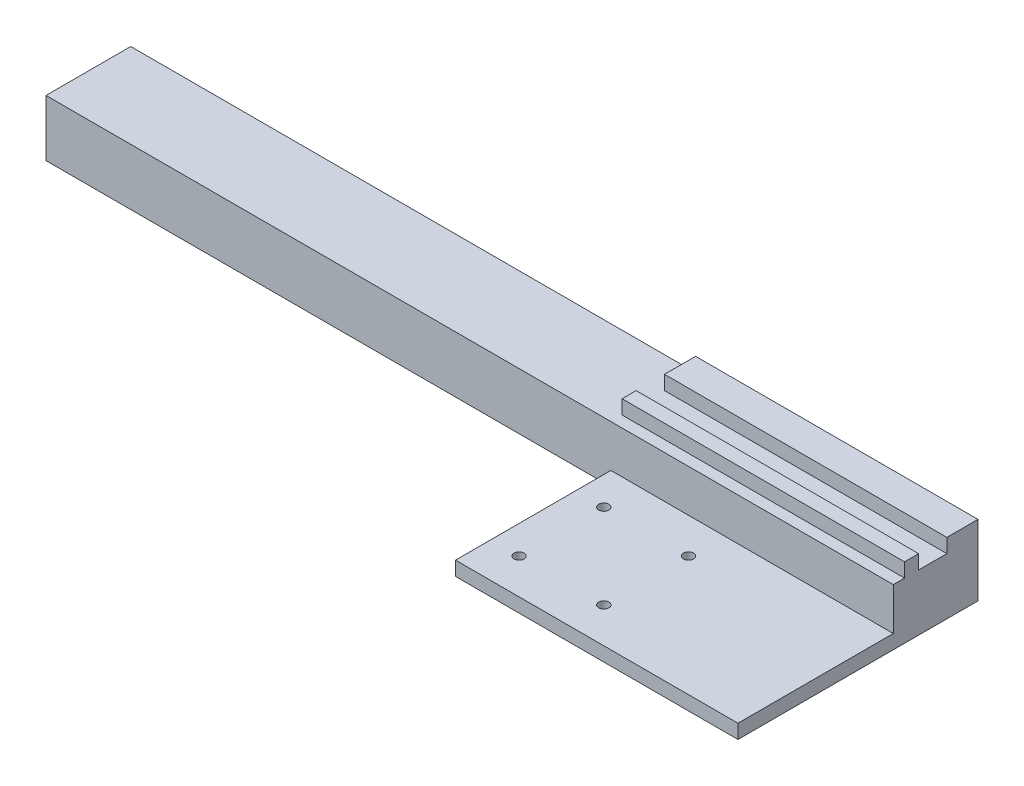
SolidWorks part; units mm, degrees
ref_plane "Front Plane" through (0, 0, 0) normal (0, 0, 1) x (1, 0, 0)
ref_plane "Top Plane" through (0, 0, 0) normal (0, 1, 0) x (1, 0, 0)
ref_plane "Right Plane" through (0, 0, 0) normal (1, 0, 0) x (0, 0, -1)
sketch "Sketch1" plane through (0, 0, 0) normal (0, 1, 0) x (1, 0, 0)
  line L1 (0, 0) -> (100, 0)
  line L2 (0, 0) -> (0, -55)
  line L3 (0, -55) -> (100, -55)
  line L4 (100, 0) -> (100, -55)
  dimension "D1" = 100
  dimension "D2" = 55
extrude "Boss-Extrude1" add sketch "Sketch1" along normal blind 5
sketch "Sketch3" plane through (0, 5, 0) normal (0, 1, 0) x (1, 0, 0)
  line L0 (100, 0) -> (0, 0) construction
  line L1 (0, -27.5) -> (100, -27.5) construction
  line L2 (0, 0) -> (0, -55) construction
  line L3 (100, -55) -> (100, 0) construction
  line L4 (50, 0) -> (50, -55) construction
  line L5 (0, -55) -> (100, -55) construction
  line L6 (25, 0) -> (25, -55) construction
  circle A0 centre (10, -12.5) radius 1.8
  dimension "D4" = 3.6
  dimension "D1" = 12.5
  dimension "D2" = 50
  dimension "D3" = 10
sketch "Sketch7" plane through (0, 0, 0) normal (0, -1, 0) x (-1, 0, 0)
  point P0 (-10, -12.5)
hole_wizard "CBORE for M3 Pan Head Machine Screw1" positions "Sketch7" profile "Sketch6" counterbore size "M3" standard "ANSI Metric" end condition through all
sketch "Sketch6" plane through (10, 0, 12.5) normal (1, 0, 0) x (0, 0, -1)
  line L0 (0, 0) -> (0, 5)
  line L1 (0, 5) -> (1.8, 5)
  line L3 (1.8, 5) -> (1.8, 2.4)
  line L4 (1.8, 2.4) -> (3.5, 2.4)
  line L5 (3.5, 2.4) -> (3.5, 0)
  line L7 (3.5, 0) -> (0, 0)
  line L11 (0, -6.35) -> (0, 107.95) construction
  dimension "Thru Hole Dia." = 3.6
  dimension "Thru Hole Depth" = 5
  dimension "C'Bore Dia." = 7
  dimension "C'Bore Depth" = 2.4
ref_plane "Plane1" through (25, 0, 0) normal (-1, 0, 0) x (0, 0, 1)
ref_plane "Plane2" through (0, 0, 27.5) normal (0, 0, 1) x (1, 0, 0)
mirror "Mirror1" about plane through (0, 0, 27.5) normal (0, 0, 1) of "CBORE for M3 Pan Head Machine Screw1" second plane through (25, 0, 0) second plane normal (-1, 0, 0)
sketch "Sketch9" plane through (0, 5, 0) normal (0, 1, 0) x (1, 0, 0)
  line L0 (100, 0) -> (0, 0) construction
  line L5 (50, 0) -> (50, -55) construction
  line L6 (50, 0) -> (100, 0)
  line L7 (100, 0) -> (100, 30)
  line L10 (50, 0) -> (-200, 0)
  line L14 (100, 30) -> (-200, 30)
  line L15 (-200, 0) -> (-200, 30)
  line L16 (50, 0) -> (100, 0)
  line L17 (100, 0) -> (-200, 0)
  line L18 (100, -55) -> (100, 0) construction
  line M11 (100, 0) -> (0, 0)
  dimension "D1" = 30
  dimension "D2" = 300
extrude "Boss-Extrude3" add sketch "Sketch9" along normal blind 15 and the other way up to surface (5 mm away) contours L15 L7 L14 M11 other way up to face at (40, 0, 39)
sketch "Sketch11" plane through (0, 20, 0) normal (0, 1, 0) x (1, 0, 0)
  line L0 (100, 0) -> (100, 30) construction
  line L1 (0, 30) -> (100, 30)
  line L2 (0, 30) -> (0, 18.98)
  line L3 (0, 18.98) -> (100, 18.98)
  line L4 (100, 30) -> (100, 18.98)
  line L6 (0, 8.98) -> (100, 8.98)
  line L7 (0, 8.98) -> (0, 3.98)
  line L8 (0, 3.98) -> (100, 3.98)
  line L9 (100, 8.98) -> (100, 3.98)
  line L11 (0, 0) -> (0, -55) construction
  line L12 (100, 30) -> (-200, 30) construction
  dimension "D1" = 11.02
  dimension "D2" = 10
  dimension "D3" = 5
extrude "Boss-Extrude5" add sketch "Sketch11" along normal blind 5
